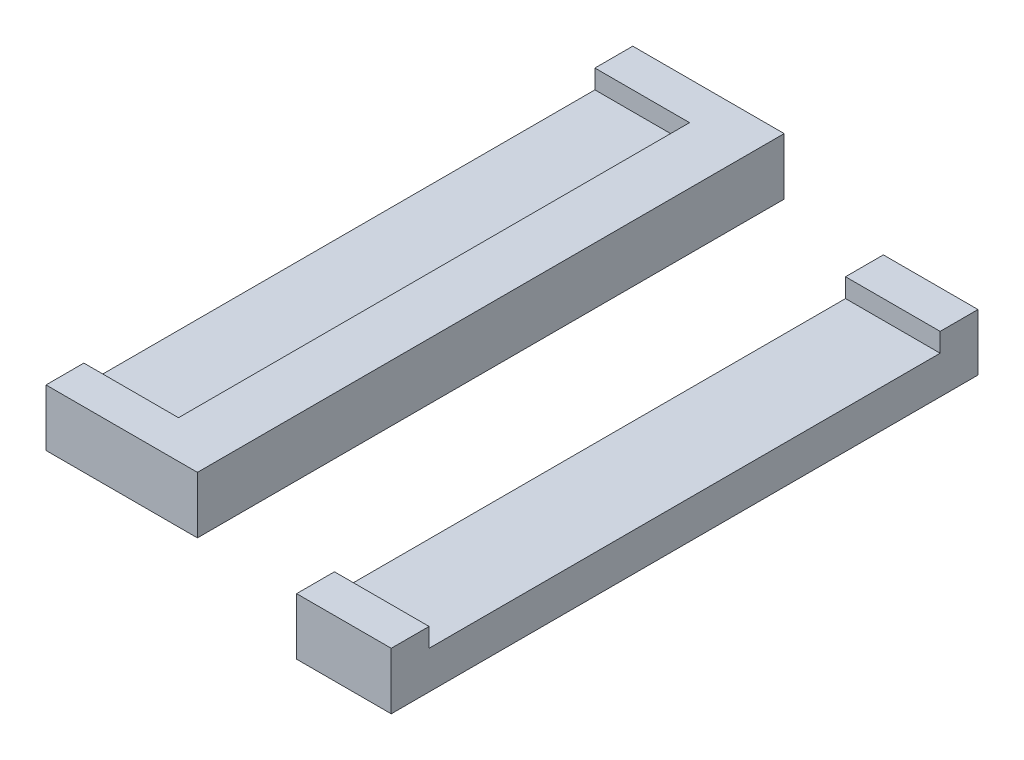
SolidWorks part; units mm, degrees
ref_plane "Front Plane" through (0, 0, 0) normal (0, 0, 1) x (1, 0, 0)
ref_plane "Top Plane" through (0, 0, 0) normal (0, 1, 0) x (1, 0, 0)
ref_plane "Right Plane" through (0, 0, 0) normal (1, 0, 0) x (0, 0, -1)
sketch "Sketch1" plane through (0, 0, 0) normal (0, 1, 0) x (1, 0, 0)
  line L1 (-12.2254, 5.2113) -> (-4.2254, 5.2113)
  line L2 (-12.2254, 5.2113) -> (-12.2254, -25.7887)
  line L3 (-12.2254, -25.7887) -> (-4.2254, -25.7887)
  line L4 (-4.2254, 5.2113) -> (-4.2254, -25.7887)
  line L5 (3.9437, 2.2817) -> (8.9437, 2.2817)
  line L6 (3.9437, 2.2817) -> (3.9437, -28.7183)
  line L7 (3.9437, -28.7183) -> (8.9437, -28.7183)
  line L8 (8.9437, 2.2817) -> (8.9437, -28.7183)
  dimension "D1" = 8
  dimension "D2" = 5
  dimension "D3" = 31
  dimension "D4" = 31
extrude "Boss-Extrude1" add sketch "Sketch1" along normal blind 2
sketch "Sketch2" plane through (0, 2, 0) normal (0, 1, 0) x (1, 0, 0)
  line L0 (-12.2254, 5.2113) -> (-12.2254, -25.7887) construction
  line L2 (-12.2254, -23.7887) -> (-12.2254, -25.7887)
  line L3 (-12.2254, -25.7887) -> (-4.2254, -25.7887)
  line L4 (-4.2254, -23.7887) -> (-4.2254, -25.7887)
  line L5 (-12.2254, 5.2113) -> (-4.2254, 5.2113)
  line L6 (-12.2254, 5.2113) -> (-12.2254, 3.2113)
  line L8 (-4.2254, 5.2113) -> (-4.2254, 3.2113)
  line L9 (3.9437, 2.2817) -> (8.9437, 2.2817)
  line L10 (3.9437, 2.2817) -> (3.9437, 0.2817)
  line L11 (3.9437, 0.2817) -> (8.9437, 0.2817)
  line L12 (8.9437, 2.2817) -> (8.9437, 0.2817)
  line L13 (3.9437, -26.7183) -> (8.9437, -26.7183)
  line L14 (3.9437, -26.7183) -> (3.9437, -28.7183)
  line L15 (3.9437, -28.7183) -> (8.9437, -28.7183)
  line L16 (8.9437, -26.7183) -> (8.9437, -28.7183)
  line L17 (-4.2254, -25.7887) -> (-4.2254, 5.2113) construction
  line L18 (-4.2254, 5.2113) -> (-12.2254, 5.2113) construction
  line L19 (-12.2254, -25.7887) -> (-4.2254, -25.7887) construction
  line L20 (3.9437, -28.7183) -> (8.9437, -28.7183) construction
  line L21 (8.9437, 2.2817) -> (3.9437, 2.2817) construction
  line L22 (3.9437, 2.2817) -> (3.9437, -28.7183) construction
  line L23 (8.9437, -28.7183) -> (8.9437, 2.2817) construction
  line L24 (-7.2254, -23.7887) -> (-12.2254, -23.7887)
  line L26 (-4.2254, 3.2113) -> (-4.2254, -23.7887)
  line L28 (-7.2254, 3.2113) -> (-7.2254, -23.7887)
  line L29 (-12.2254, 3.2113) -> (-7.2254, 3.2113)
  point P18 (-12.2254, 4.2113)
  dimension "D1" = 2
  dimension "D2" = 3
extrude "Boss-Extrude2" add sketch "Sketch2" along normal blind 1
